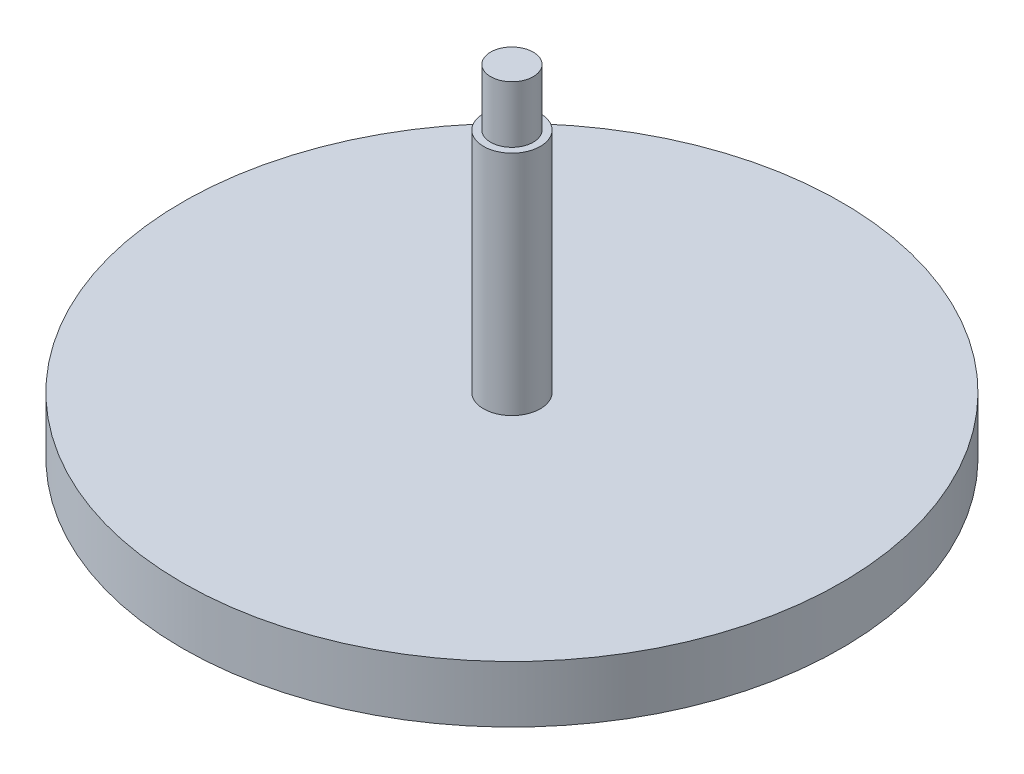
SolidWorks part; units mm, degrees
ref_plane "Front Plane" through (0, 0, 0) normal (0, 0, 1) x (1, 0, 0)
ref_plane "Top Plane" through (0, 0, 0) normal (0, 1, 0) x (1, 0, 0)
ref_plane "Right Plane" through (0, 0, 0) normal (1, 0, 0) x (0, 0, -1)
sketch "Sketch1" plane through (0, 0, 0) normal (0, 1, 0) x (1, 0, 0)
  circle A0 centre (0, 0) radius 116
  dimension "D1" = 232
extrude "Boss-Extrude1" add sketch "Sketch1" along normal blind 20
sketch "Sketch2" plane through (0, 20, 0) normal (0, 1, 0) x (1, 0, 0)
  circle A0 centre (0, 0) radius 10
  dimension "D1" = 20
extrude "Boss-Extrude2" add sketch "Sketch2" along normal blind 100
sketch "Sketch3" plane through (0, 120, 0) normal (0, 1, 0) x (1, 0, 0)
  circle A0 centre (0, 0) radius 7.5
  dimension "D1" = 15
extrude "Cut-Extrude1" cut sketch "Sketch3" against normal blind 20 flip side to cut
